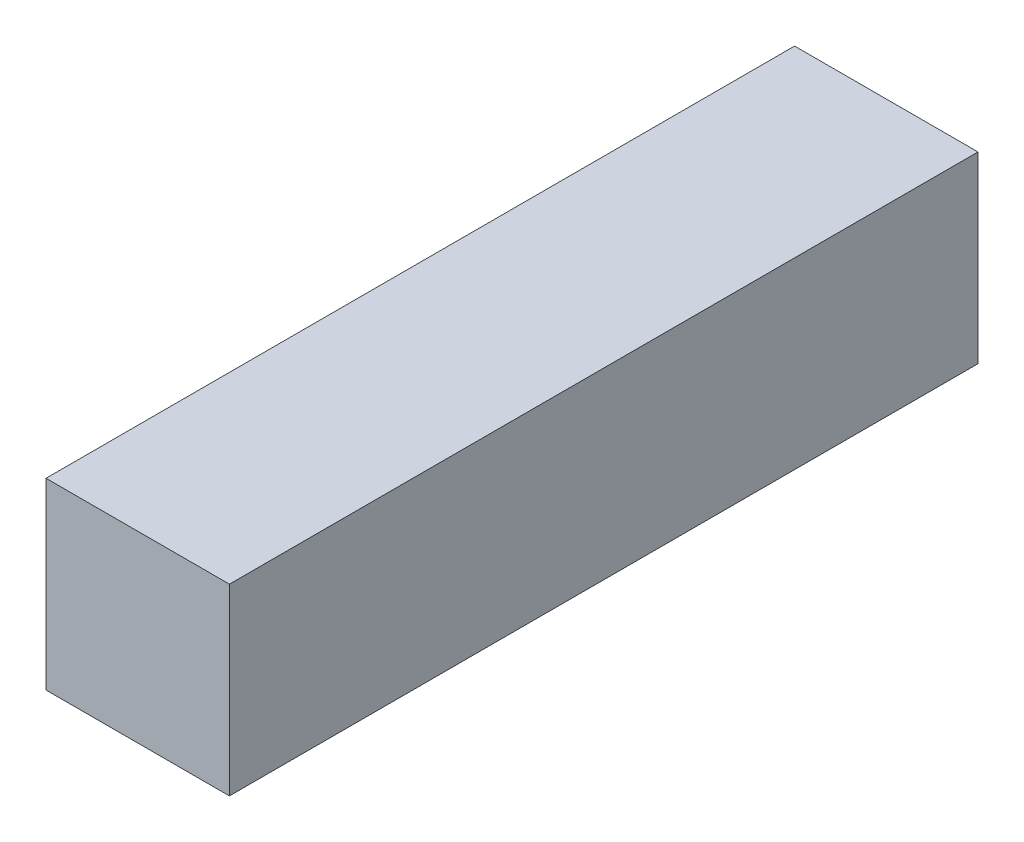
SolidWorks part; units mm, degrees
ref_plane "Front Plane" through (0, 0, 0) normal (0, 0, 1) x (1, 0, 0)
ref_plane "Top Plane" through (0, 0, 0) normal (0, 1, 0) x (1, 0, 0)
ref_plane "Right Plane" through (0, 0, 0) normal (1, 0, 0) x (0, 0, -1)
sketch "Sketch1" plane through (0, 0, 0) normal (0, 0, 1) x (1, 0, 0)
  line L1 (-2.45, -2.45) -> (2.45, -2.45)
  line L2 (-2.45, -2.45) -> (-2.45, 2.45)
  line L3 (-2.45, 2.45) -> (2.45, 2.45)
  line L4 (2.45, -2.45) -> (2.45, 2.45)
  line L5 (-2.45, -2.45) -> (2.45, 2.45) construction
  line L6 (-2.45, 2.45) -> (2.45, -2.45) construction
  point P0 (0, 0)
  dimension "D1" = 4.9
  dimension "D2" = 4.9
extrude "Boss-Extrude1" add sketch "Sketch1" along normal blind 20
